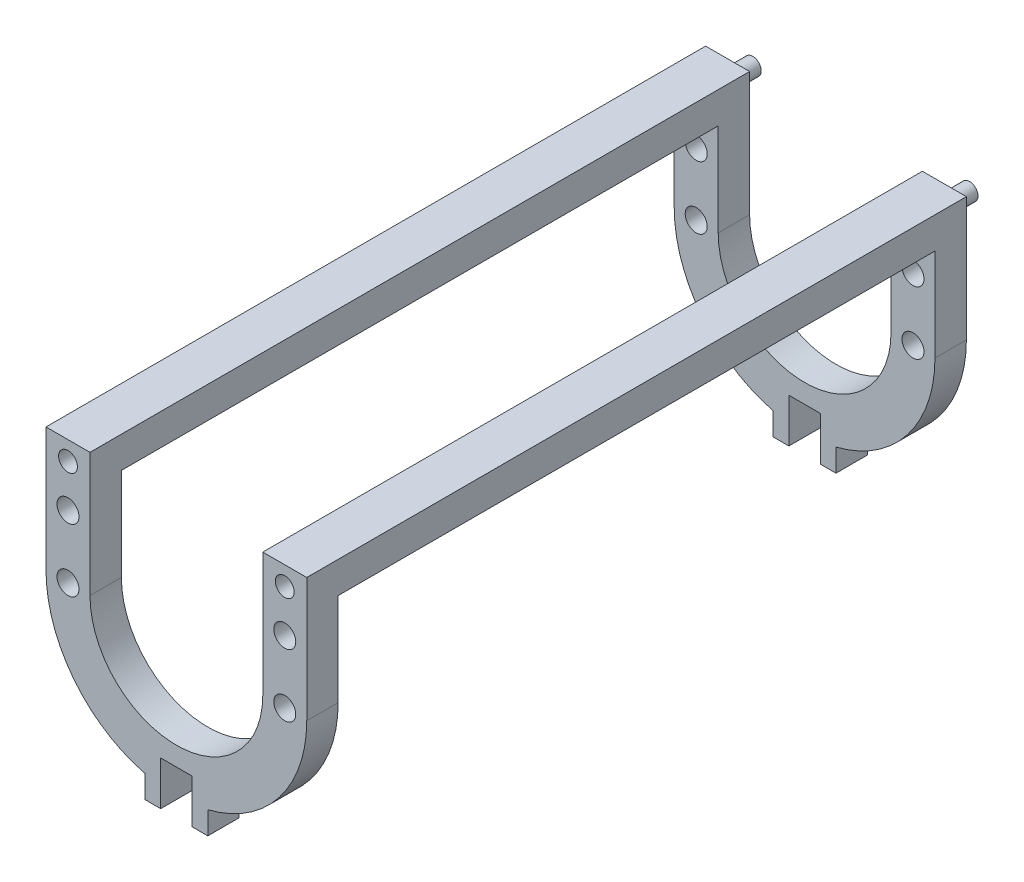
SolidWorks part; units mm, degrees
ref_plane "Front Plane" through (0, 0, 0) normal (0, 0, 1) x (1, 0, 0)
ref_plane "Top Plane" through (0, 0, 0) normal (0, 1, 0) x (1, 0, 0)
ref_plane "Right Plane" through (0, 0, 0) normal (1, 0, 0) x (0, 0, -1)
sketch "Sketch1" plane through (0, 0, 0) normal (0, 0, 1) x (1, 0, 0)
  line L9 (-20.7532, 19.75) -> (-20.7532, 0)
  line L10 (-5, -20.1419) -> (-5, -23.7532)
  line L11 (-5, -23.7532) -> (-2.5, -23.7532)
  line L12 (5, -23.7532) -> (5, -20.1419)
  line L13 (20.7532, 0) -> (20.7532, 19.75)
  line L14 (20.7532, 19.75) -> (13.7532, 19.75)
  line L15 (13.7532, 19.75) -> (13.7532, 0)
  line L16 (-13.7532, 0) -> (-13.7532, 19.75)
  line L17 (-13.7532, 19.75) -> (-20.7532, 19.75)
  line L18 (-20.7532, 19.75) -> (-20.7532, 0)
  line L19 (-5, -20.1419) -> (-5, -23.7532)
  line L20 (-5, -23.7532) -> (-2.5, -23.7532)
  line L21 (5, -23.7532) -> (5, -20.1419)
  line L22 (20.7532, 0) -> (20.7532, 19.75)
  line L23 (20.7532, 19.75) -> (13.7532, 19.75)
  line L24 (13.7532, 19.75) -> (13.7532, 0)
  line L25 (-13.7532, 0) -> (-13.7532, 19.75)
  line L26 (-13.7532, 19.75) -> (-20.7532, 19.75)
  line L44 (-2.5, -23.7532) -> (-2.5, -16.7532)
  line L45 (-2.5, -23.7532) -> (-2.5, -16.7532)
  line L46 (-2.5, -16.7532) -> (2.5, -16.7532)
  line L47 (-2.5, -16.7532) -> (2.5, -16.7532)
  line L48 (2.5, -16.7532) -> (2.5, -23.7532)
  line L49 (2.5, -16.7532) -> (2.5, -23.7532)
  line L50 (2.5, -23.7532) -> (5, -23.7532)
  line L51 (2.5, -23.7532) -> (5, -23.7532)
  circle A0 centre (-17.2532, 10) radius 1.75 construction
  circle A1 centre (-17.2532, 0) radius 1.75 construction
  circle A2 centre (17.2532, 0) radius 1.75 construction
  arc A3 (-20.7532, 0) -> (-5, -20.1419) centre (0, 0) ccw
  arc A4 (5, -20.1419) -> (20.7532, 0) centre (0, 0) ccw
  arc A5 (-13.7532, 0) -> (13.7532, 0) centre (0, 0) ccw
  arc A6 (-20.7532, 0) -> (-5, -20.1419) centre (0, 0) ccw
  arc A7 (5, -20.1419) -> (20.7532, 0) centre (0, 0) ccw
  arc A8 (-13.7532, 0) -> (13.7532, 0) centre (0, 0) ccw
  circle A9 centre (17.2532, 10) radius 1.75 construction
  circle A10 centre (-17.2532, 10) radius 1.75
  circle A11 centre (-17.2532, 0) radius 1.75
  circle A12 centre (17.2532, 0) radius 1.75
  circle A13 centre (17.2532, 10) radius 1.75
  dimension "D1" = 0
extrude "Boss-Extrude1" add sketch "Sketch1" along normal blind 5
sketch "Sketch2" plane through (0, 0, 0) normal (0, 0, -1) x (-1, 0, 0)
  circle A0 centre (17.2532, 16.75) radius 1.35
  circle A1 centre (-17.2532, 16.75) radius 1.35
  dimension "D1" = 2.7
  dimension "D2" = 2.7
extrude "Boss-Extrude2" add sketch "Sketch2" along normal blind 4
sketch "Sketch4" plane through (0, 0, 0) normal (0, 0, -1) x (-1, 0, 0)
  line L0 (20.7532, 19.75) -> (20.7532, 0) construction
  line L1 (13.7532, 19.75) -> (20.7532, 19.75)
  line L2 (13.7532, 19.75) -> (13.7532, 14.75)
  line L3 (13.7532, 14.75) -> (20.7532, 14.75)
  line L4 (20.7532, 19.75) -> (20.7532, 14.75)
  line L5 (20.7532, 14.75) -> (13.7532, 14.75) construction
  line L6 (-13.7532, 19.75) -> (-13.7532, 0) construction
  line L7 (-20.7532, 19.75) -> (-13.7532, 19.75)
  line L8 (-20.7532, 19.75) -> (-20.7532, 14.75)
  line L9 (-20.7532, 14.75) -> (-13.7532, 14.75)
  line L10 (-13.7532, 19.75) -> (-13.7532, 14.75)
  line L11 (-13.7532, 14.75) -> (-20.7532, 14.75) construction
extrude "Boss-Extrude3" add sketch "Sketch4" against normal blind 105
sketch "Sketch5" plane through (0, 0, 105) normal (0, 0, 1) x (1, 0, 0)
  line L9 (20.7532, 14.75) -> (13.7532, 14.75)
  line L10 (13.7532, 14.75) -> (13.7532, 0)
  line L11 (-13.7532, 0) -> (-13.7532, 14.75)
  line L12 (-13.7532, 14.75) -> (-20.7532, 14.75)
  line L13 (-20.7532, 14.75) -> (-20.7532, 0)
  line L14 (-5, -20.1419) -> (-5, -23.7532)
  line L15 (-5, -23.7532) -> (-2.5, -23.7532)
  line L16 (5, -23.7532) -> (5, -20.1419)
  line L17 (20.7532, 0) -> (20.7532, 14.75)
  line L18 (20.7532, 14.75) -> (13.7532, 14.75)
  line L19 (13.7532, 14.75) -> (13.7532, 0)
  line L20 (-13.7532, 0) -> (-13.7532, 14.75)
  line L21 (-13.7532, 14.75) -> (-20.7532, 14.75)
  line L22 (-20.7532, 14.75) -> (-20.7532, 0)
  line L23 (-5, -20.1419) -> (-5, -23.7532)
  line L24 (-5, -23.7532) -> (-2.5, -23.7532)
  line L25 (5, -23.7532) -> (5, -20.1419)
  line L26 (20.7532, 0) -> (20.7532, 14.75)
  line L31 (-2.5, -23.7532) -> (-2.5, -16.7532)
  line L32 (-2.5, -23.7532) -> (-2.5, -16.7532)
  line L33 (-2.5, -16.7532) -> (2.5, -16.7532)
  line L34 (-2.5, -16.7532) -> (2.5, -16.7532)
  line L35 (2.5, -16.7532) -> (2.5, -23.7532)
  line L36 (2.5, -16.7532) -> (2.5, -23.7532)
  line L37 (2.5, -23.7532) -> (5, -23.7532)
  line L38 (2.5, -23.7532) -> (5, -23.7532)
  circle A0 centre (17.2532, 10) radius 1.75 construction
  circle A1 centre (-17.2532, 10) radius 1.75 construction
  circle A2 centre (-17.2532, 0) radius 1.75 construction
  arc A3 (-13.7532, 0) -> (13.7532, 0) centre (0, 0) ccw
  arc A4 (-20.7532, 0) -> (-5, -20.1419) centre (0, 0) ccw
  arc A5 (5, -20.1419) -> (20.7532, 0) centre (0, 0) ccw
  arc A6 (-13.7532, 0) -> (13.7532, 0) centre (0, 0) ccw
  arc A7 (-20.7532, 0) -> (-5, -20.1419) centre (0, 0) ccw
  arc A8 (5, -20.1419) -> (20.7532, 0) centre (0, 0) ccw
  circle A9 centre (17.2532, 0) radius 1.75 construction
  circle A10 centre (17.2532, 10) radius 1.75
  circle A11 centre (-17.2532, 10) radius 1.75
  circle A12 centre (-17.2532, 0) radius 1.75
  circle A13 centre (17.2532, 0) radius 1.75
  dimension "D1" = 0
extrude "Boss-Extrude4" add sketch "Sketch5" against normal blind 5
sketch "Sketch6" plane through (0, 0, 105) normal (0, 0, 1) x (1, 0, 0)
  circle A1 centre (17.2532, 16.75) radius 1.35
  circle A2 centre (17.2532, 16.75) radius 1.35
  circle A3 centre (-17.2532, 16.75) radius 1.35
  circle A4 centre (-17.2532, 16.75) radius 1.35
  dimension "D1" = 0
  dimension "D2" = 0
extrude "Cut-Extrude1" cut sketch "Sketch6" against normal blind 5
sketch "Sketch8" plane through (0, 0, 105) normal (0, 0, 1) x (1, 0, 0)
  circle A0 centre (17.2532, 16.75) radius 1.5
  circle A1 centre (-17.2532, 16.75) radius 1.5
  dimension "D1" = 3
  dimension "D2" = 3
extrude "Cut-Extrude3" cut sketch "Sketch8" against normal blind 5
